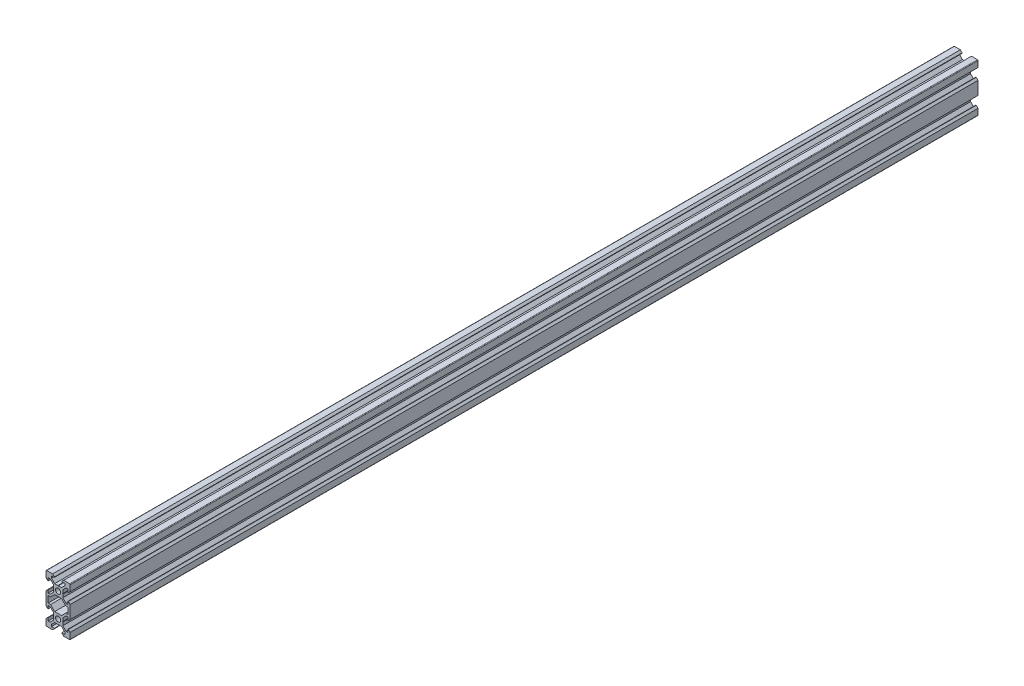
SolidWorks part; units mm, degrees
material "6061-T6 (SS)"
ref_plane "Front Plane" through (0, 0, 0) normal (0, 0, 1) x (1, 0, 0)
ref_plane "Top Plane" through (0, 0, 0) normal (0, 1, 0) x (1, 0, 0)
ref_plane "Right Plane" through (0, 0, 0) normal (1, 0, 0) x (0, 0, -1)
sketch "Sketch1" plane through (0, 0, 0) normal (0, 0, 1) x (1, 0, 0)
  line L0 (0, 0) -> (10, 0) construction
  line L1 (9.5, -20) -> (-9.5, -20)
  line L2 (10, -19.5) -> (10, 19.5)
  line L3 (9.5, 20) -> (-9.5, 20)
  line L4 (-10, -19.5) -> (-10, 19.5)
  line L5 (10, -20) -> (-10, 20) construction
  line L6 (10, 20) -> (-10, -20) construction
  circle A0 centre (0, 10) radius 2.1
  circle A1 centre (0, -10) radius 2.1
  arc A2 (-9.5, -20) -> (-10, -19.5) centre (-9.5, -19.5) cw
  arc A3 (9.5, -20) -> (10, -19.5) centre (9.5, -19.5) ccw
  arc A4 (10, 19.5) -> (9.5, 20) centre (9.5, 19.5) ccw
  arc A5 (-9.5, 20) -> (-10, 19.5) centre (-9.5, 19.5) ccw
  point P0 (0, 0)
  line B0 (0, 10) -> (0, 20) construction
  line B1 (0, 13.69) -> (-0.21, 13.9)
  line B2 (-0.21, 13.9) -> (-2.8393, 13.9)
  line B3 (-2.8393, 13.9) -> (-5.5, 16.5607)
  line B4 (-5.5, 16.5607) -> (-5.5, 18.2)
  line B5 (-5.5, 18.2) -> (-3.125, 18.2)
  line B6 (-3.125, 18.2) -> (-3.125, 18.545)
  line B7 (-3.125, 18.545) -> (-4.58, 20)
  line B8 (-4.58, 20) -> (4.58, 20)
  line B9 (0, 10) -> (-5.9132, 15.9132) construction
  line B10 (3.125, 18.545) -> (4.58, 20)
  line B11 (3.125, 18.2) -> (3.125, 18.545)
  line B12 (5.5, 18.2) -> (3.125, 18.2)
  line B13 (5.5, 16.5607) -> (5.5, 18.2)
  line B14 (2.8393, 13.9) -> (5.5, 16.5607)
  line B15 (0.21, 13.9) -> (2.8393, 13.9)
  line B16 (0, 13.69) -> (0.21, 13.9)
  line B17 (0, 10) -> (-10, 10) construction
  line B18 (-3.69, 10) -> (-3.9, 9.79)
  line B19 (-3.9, 9.79) -> (-3.9, 7.1607)
  line B20 (-3.9, 7.1607) -> (-6.5607, 4.5)
  line B21 (-6.5607, 4.5) -> (-8.2, 4.5)
  line B22 (-8.2, 4.5) -> (-8.2, 6.875)
  line B23 (-8.2, 6.875) -> (-8.545, 6.875)
  line B24 (-8.545, 6.875) -> (-10, 5.42)
  line B25 (-10, 5.42) -> (-10, 14.58)
  line B26 (0, 10) -> (-5.9132, 4.0868) construction
  line B27 (-8.545, 13.125) -> (-10, 14.58)
  line B28 (-8.2, 13.125) -> (-8.545, 13.125)
  line B29 (-8.2, 15.5) -> (-8.2, 13.125)
  line B30 (-6.5607, 15.5) -> (-8.2, 15.5)
  line B31 (-3.9, 12.8393) -> (-6.5607, 15.5)
  line B32 (-3.9, 10.21) -> (-3.9, 12.8393)
  line B33 (-3.69, 10) -> (-3.9, 10.21)
  line B34 (0, -10) -> (-10, -10) construction
  line B35 (-3.69, -10) -> (-3.9, -10.21)
  line B36 (-3.9, -10.21) -> (-3.9, -12.8393)
  line B37 (-3.9, -12.8393) -> (-6.5607, -15.5)
  line B38 (-6.5607, -15.5) -> (-8.2, -15.5)
  line B39 (-8.2, -15.5) -> (-8.2, -13.125)
  line B40 (-8.2, -13.125) -> (-8.545, -13.125)
  line B41 (-8.545, -13.125) -> (-10, -14.58)
  line B42 (-10, -14.58) -> (-10, -5.42)
  line B43 (0, -10) -> (-5.9132, -15.9132) construction
  line B44 (-8.545, -6.875) -> (-10, -5.42)
  line B45 (-8.2, -6.875) -> (-8.545, -6.875)
  line B46 (-8.2, -4.5) -> (-8.2, -6.875)
  line B47 (-6.5607, -4.5) -> (-8.2, -4.5)
  line B48 (-3.9, -7.1607) -> (-6.5607, -4.5)
  line B49 (-3.9, -9.79) -> (-3.9, -7.1607)
  line B50 (-3.69, -10) -> (-3.9, -9.79)
  line B51 (0, -10) -> (0, -20) construction
  line B52 (0, -13.69) -> (0.21, -13.9)
  line B53 (0.21, -13.9) -> (2.8393, -13.9)
  line B54 (2.8393, -13.9) -> (5.5, -16.5607)
  line B55 (5.5, -16.5607) -> (5.5, -18.2)
  line B56 (5.5, -18.2) -> (3.125, -18.2)
  line B57 (3.125, -18.2) -> (3.125, -18.545)
  line B58 (3.125, -18.545) -> (4.58, -20)
  line B59 (4.58, -20) -> (-4.58, -20)
  line B60 (0, -10) -> (5.9132, -15.9132) construction
  line B61 (-3.125, -18.545) -> (-4.58, -20)
  line B62 (-3.125, -18.2) -> (-3.125, -18.545)
  line B63 (-5.5, -18.2) -> (-3.125, -18.2)
  line B64 (-5.5, -16.5607) -> (-5.5, -18.2)
  line B65 (-2.8393, -13.9) -> (-5.5, -16.5607)
  line B66 (-0.21, -13.9) -> (-2.8393, -13.9)
  line B67 (0, -13.69) -> (-0.21, -13.9)
  line B68 (0, -10) -> (10, -10) construction
  line B69 (3.69, -10) -> (3.9, -9.79)
  line B70 (3.9, -9.79) -> (3.9, -7.1607)
  line B71 (3.9, -7.1607) -> (6.5607, -4.5)
  line B72 (6.5607, -4.5) -> (8.2, -4.5)
  line B73 (8.2, -4.5) -> (8.2, -6.875)
  line B74 (8.2, -6.875) -> (8.545, -6.875)
  line B75 (8.545, -6.875) -> (10, -5.42)
  line B76 (10, -5.42) -> (10, -14.58)
  line B77 (0, -10) -> (5.9132, -4.0868) construction
  line B78 (8.545, -13.125) -> (10, -14.58)
  line B79 (8.2, -13.125) -> (8.545, -13.125)
  line B80 (8.2, -15.5) -> (8.2, -13.125)
  line B81 (6.5607, -15.5) -> (8.2, -15.5)
  line B82 (3.9, -12.8393) -> (6.5607, -15.5)
  line B83 (3.9, -10.21) -> (3.9, -12.8393)
  line B84 (3.69, -10) -> (3.9, -10.21)
  line B85 (0, 10) -> (10, 10) construction
  line B86 (3.69, 10) -> (3.9, 10.21)
  line B87 (3.9, 10.21) -> (3.9, 12.8393)
  line B88 (3.9, 12.8393) -> (6.5607, 15.5)
  line B89 (6.5607, 15.5) -> (8.2, 15.5)
  line B90 (8.2, 15.5) -> (8.2, 13.125)
  line B91 (8.2, 13.125) -> (8.545, 13.125)
  line B92 (8.545, 13.125) -> (10, 14.58)
  line B93 (10, 14.58) -> (10, 5.42)
  line B94 (0, 10) -> (5.9132, 15.9132) construction
  line B95 (8.545, 6.875) -> (10, 5.42)
  line B96 (8.2, 6.875) -> (8.545, 6.875)
  line B97 (8.2, 4.5) -> (8.2, 6.875)
  line B98 (6.5607, 4.5) -> (8.2, 4.5)
  line B99 (3.9, 7.1607) -> (6.5607, 4.5)
  line B100 (3.9, 9.79) -> (3.9, 7.1607)
  line B101 (3.69, 10) -> (3.9, 9.79)
  line B102 (-8.2, -2.7) -> (-8.2, 2.7)
  line B103 (-8.2, 2.7) -> (-6.2393, 2.7)
  line B104 (-6.2393, 2.7) -> (-2.8393, 6.1)
  line B105 (-2.8393, 6.1) -> (2.8393, 6.1)
  line B106 (0, 6.1) -> (0, 0) construction
  line B107 (0, 0) -> (-8.2, 0) construction
  line B108 (6.2393, 2.7) -> (2.8393, 6.1)
  line B109 (8.2, 2.7) -> (6.2393, 2.7)
  line B110 (8.2, -2.7) -> (8.2, 2.7)
  line B111 (8.2, -2.7) -> (6.2393, -2.7)
  line B112 (6.2393, -2.7) -> (2.8393, -6.1)
  line B113 (-2.8393, -6.1) -> (2.8393, -6.1)
  line B114 (-6.2393, -2.7) -> (-2.8393, -6.1)
  line B115 (-8.2, -2.7) -> (-6.2393, -2.7)
  line B116 (0, 6.1) -> (0, 10) construction
  line B117 (0, 10) -> (-5.0927, 4.9073) construction
  dimension "D4" = 4.2
  dimension "D5" = 0.5
  dimension "D1" = 20
  dimension "D2" = 40
  dimension "D3" = 20
sketch_block_instance "V Slot 1-4"
sketch_block "V Slot 1" parameters "D1"=10, "D2"=11, "D3"=4.3, "D4"=1.8, "D5"=0.21, "D6"=45, "D7"=9.16, "D8"=1.5, "D9"=6.25
sketch_block_instance "V Slot 1-5"
sketch_block_instance "V Slot 1-6"
sketch_block_instance "V Slot 1-7"
sketch_block_instance "V Slot 1-8"
sketch_block_instance "V Slot 1-9"
sketch_block_instance "Center Cutout 1-1"
sketch_block "Center Cutout 1" parameters "D1"=5.4, "D2"=12.2, "D3"=8.2, "D4"=45, "D5"=10, "D6"=1.5
extrude "Boss-Extrude1" add sketch "Sketch1" along normal blind 750 contours B101 B86 B87 B88 B89 B90 B91 B92 L2 A4 L3 B10 B11 B12 B13 B14 B15 B16 B1 B2 B3 B4 B5 B6 B7 A5 L4 B27 B28 B29 B30 B31 B32 B33 B18 B19 B20 B21 B22 B23 B24 B44 B45 B46 B47 B48 B49 B50 B35
